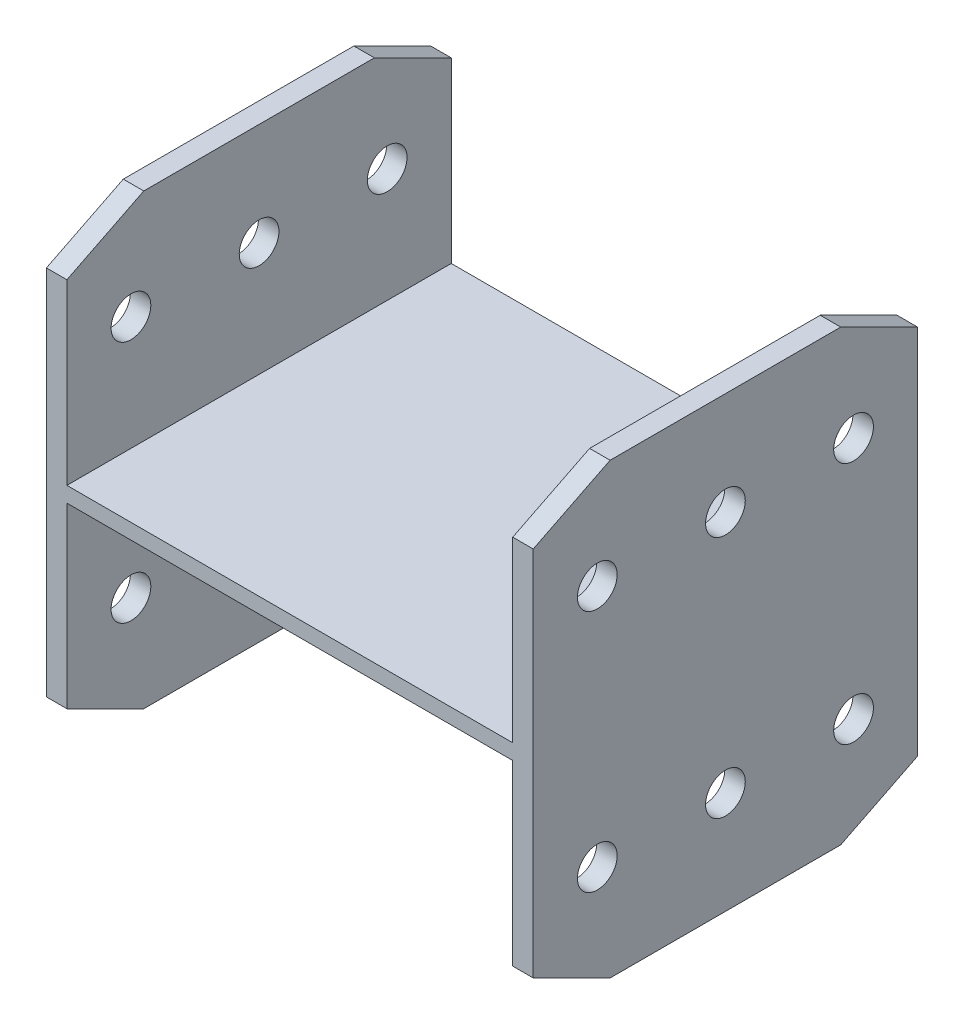
SolidWorks part; units mm, degrees
ref_plane "前视基准面" through (0, 0, 0) normal (0, 0, 1) x (1, 0, 0)
ref_plane "上视基准面" through (0, 0, 0) normal (0, 1, 0) x (1, 0, 0)
ref_plane "右视基准面" through (0, 0, 0) normal (1, 0, 0) x (0, 0, -1)
sketch "草图1" plane through (0, 0, 0) normal (0, 0, 1) x (1, 0, 0)
  line L0 (-174, -6) -> (174, -6)
  line L1 (174, 6) -> (174, 175)
  line L2 (174, 175) -> (190, 175)
  line L3 (190, 175) -> (190, -175)
  line L4 (190, -175) -> (174, -175)
  line L5 (174, -175) -> (174, -6)
  line L6 (174, 6) -> (-174, 6)
  line L7 (-174, -6) -> (-174, -175)
  line L8 (-174, -175) -> (-190, -175)
  line L9 (-190, -175) -> (-190, 175)
  line L10 (-190, 175) -> (-174, 175)
  line L11 (-174, 175) -> (-174, 6)
  line L13 (-65.4624, 0) -> (81.5699, 0) construction
  line L15 (0, 49.7569) -> (0, -54.2333) construction
  dimension "D1" = 350
  dimension "D2" = 12
  dimension "D3" = 16
  dimension "D4" = 380
extrude "拉伸1" add sketch "草图1" along normal mid plane 300
sketch "草图2" plane through (190, 0, 0) normal (1, 0, 0) x (0, 0, -1)
  line L0 (-150, 175) -> (150, 175) construction
  line L1 (-150, 0) -> (49850, 0) construction
  line L2 (150, -175) -> (150, 175) construction
  line L4 (0, 186.0956) -> (0, -194.143) construction
  line L5 (-150, -175) -> (-150, 175) construction
  circle A0 centre (-100, 95) radius 15.5
  circle A1 centre (0, 95) radius 15.5
  circle A2 centre (100, 95) radius 15.5
  circle A3 centre (100, -95) radius 15.5
  circle A4 centre (0, -95) radius 15.5
  circle A5 centre (-100, -95) radius 15.5
  point P8 (-150, 0)
  point P24 (150, 0)
  dimension "D1" = 31
  dimension "D2" = 80
  dimension "D3" = 100
  dimension "D4" = 50
extrude "拉伸7" cut sketch "草图2" against normal through all
sketch "草图3" plane through (0, 0, 0) normal (1, 0, 0) x (0, 0, -1)
  line L0 (-150, 175) -> (-90, 175)
  line L1 (-150, 175) -> (150, 175) construction
  line L2 (-90, 175) -> (-150, 145)
  line L3 (-150, -175) -> (-150, 175) construction
  line L4 (-150, 145) -> (-150, 175)
  line L6 (-183.8399, 0) -> (233.2826, 0) construction
  line L8 (0, 184.0838) -> (0, -189.4487) construction
  line L9 (150, 145) -> (150, 175)
  line L10 (150, 175) -> (90, 175)
  line L11 (90, 175) -> (150, 145)
  line L12 (150, -175) -> (90, -175)
  line L13 (90, -175) -> (150, -145)
  line L14 (150, -145) -> (150, -175)
  line L15 (-150, -145) -> (-150, -175)
  line L16 (-150, -175) -> (-90, -175)
  line L17 (-90, -175) -> (-150, -145)
  dimension "D1" = 60
  dimension "D2" = 30
extrude "拉伸8" cut sketch "草图3" against normal through all and the other way through all
